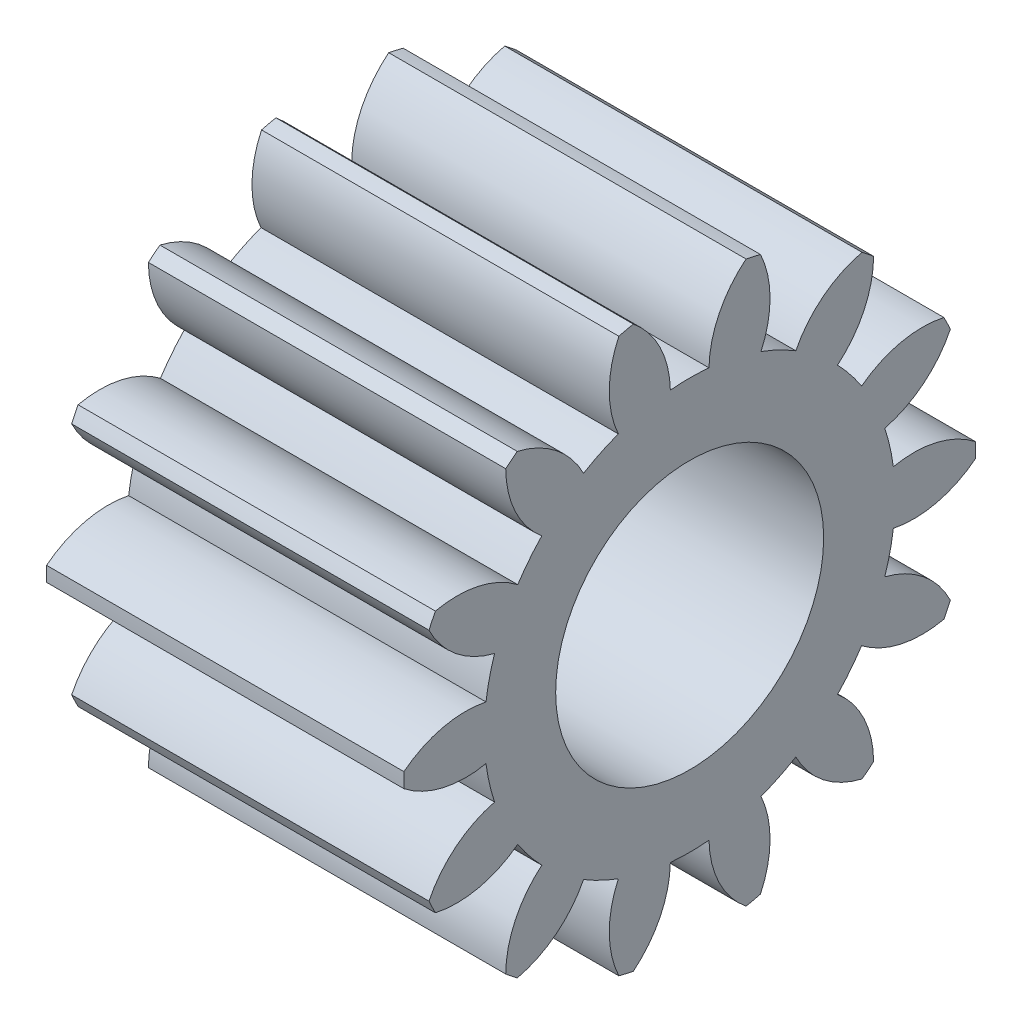
SolidWorks part; units mm, degrees
ref_plane "Plane1" through (0, 0, 0) normal (0, 0, 1) x (1, 0, 0)
ref_plane "Plane2" through (0, 0, 0) normal (0, 1, 0) x (1, 0, 0)
ref_plane "Plane3" through (0, 0, 0) normal (1, 0, 0) x (0, 0, -1)
other "Configuration Table"
sketch "HoldingSke" plane through (0, 0, 0) normal (0, 1, 0) x (1, 0, 0)
  line L0 (0, 0) -> (0.9703, -0.2419)
  line L1 (-15, 0) -> (100, 0) construction
  line L2 (0, 0) -> (-2.1039, 2.3779)
  line L3 (0, 0) -> (-11.863, 4.5341)
  line L4 (0, 0) -> (8.3795, 2.0892)
  line L5 (0, 0) -> (-46.8476, -17.4728)
  line L6 (0, 0) -> (-8.2896, -5.593)
  line L7 (-2.1039, 2.3779) -> (8.6586, 51.2059)
  line L8 (-76.2, 54.61) -> (-76.1, 54.61)
  line L9 (-71.009, 38.7566) -> (-53.1078, 45.2721)
  line L10 (-76.2, 71.12) -> (104.1128, 71.12)
  line L11 (0, 0) -> (-10, 0)
  line L12 (-76.2, 101.6) -> (-76.162, 101.6)
  line L13 (24.9733, 27.94) -> (52.9518, 28.4284)
  line L14 (24.9733, 27.94) -> (24.9743, 27.94)
  line L15 (24.9733, 27.94) -> (100.4006, 29.5858)
  line L16 (-63.627, -1) -> (-12.827, -1)
  circle A0 centre (0, 0) radius 0.5
  circle A1 centre (0, 0) radius 5.749
  circle A2 centre (0, 0) radius 37.5
  circle A3 centre (0, 0) radius 0.5
  dimension "MHD" = 11.498
  dimension "Hub_dia" = 75
  dimension "Bore" = 1
  dimension "MBD" = 1
  dimension "Num_teeth" = 14
  dimension "Pitch" = 1
  dimension "Overall_len" = 50
  dimension "Show_teeth" = 14
  dimension "Thickness" = 10
  dimension "OAL" = 50.0001
  dimension "T_dim" = 0.1
  dimension "Ap" = 20
  dimension "H" = 19.05
  dimension "Pitch_radius" = 180.3128
  dimension "Width" = 10
  dimension "Backlash" = 0.038
  dimension "Addendum_fac" = 1
  dimension "Dedendum_fac" = 1.25
  dimension "Clearance_fac" = 0.25
  dimension "Dedendum_add" = 0.001
  dimension "Module" = 1
sketch "BasProSke" plane through (0, 0, 0) normal (0, 1, 0) x (1, 0, 0)
  line L0 (-10, 0) -> (60, 0) construction
  line L1 (0, 0) -> (0, 8)
  line L2 (0, 0) -> (10, 0)
  line L3 (10, 0) -> (10, 8)
  line L4 (10, 8) -> (0, 8)
  dimension "Thickness" = 10
  dimension "Diameter" = 16
revolve "Base-Revolve" add sketch "BasProSke" angle 360 about L0
sketch "TooCutSke" plane through (0, 0, 0) normal (1, 0, 0) x (0, 0, -1)
  line L1 (0, 0) -> (0, 107) construction
  line L2 (0, 0) -> (-0.8502, 6.9482) construction
  line L3 (0, 0) -> (-3.0989, 13.5772) construction
  line L4 (-0.8502, 6.9482) -> (-1.5494, 6.7886) construction
  arc A0 (0.5404, 5.7235) -> (-0.5404, 5.7235) centre (0, 0) ccw
  arc A1 (1.6036, 7.8636) -> (-1.6036, 7.8636) centre (0, 0) ccw
  circle A2 centre (0, 0) radius 7 construction
  circle A3 centre (0, 0) radius 6.5778 construction
  arc A4 (-0.5404, 5.7235) -> (-1.6036, 7.8636) centre (-3.3398, 5.6669) ccw
  arc A5 (1.6036, 7.8636) -> (0.5404, 5.7235) centre (3.3398, 5.6669) ccw
  dimension "Root_dia" = 11.498
  dimension "Overcut_dia" = 16.0508
  dimension "Pitch_dia" = 14
  dimension "Base_dia" = 13.1557
  dimension "Flank_rad" = 2.8
  dimension "Half_ang" = 12.857
  dimension "Half_CT" = 0.7173
extrude "ToothCut" cut sketch "TooCutSke" along normal through all
fillet "Breaks" [suppressed] radius 0.02
fillet "RootFillets" [suppressed] radius 0.251
pattern_circular "TeethCuts" count 14 every 25.714 about axis through (-10, 0, 0) along (1, 0, 0) of "ToothCut", "RootFillets", "Breaks"
sketch "HubNeaOneSke" plane through (0, 0, 0) normal (-1, 0, 0) x (0, 0, 1)
  circle A0 centre (0, 0) radius 5.749
  dimension "Diameter" = 11.498
extrude "HubNearOne" [suppressed] add sketch "HubNeaOneSke" along normal blind 40.0001
sketch "HubNeaBotSke" plane through (0, 0, 0) normal (-1, 0, 0) x (0, 0, 1)
  circle A0 centre (0, 0) radius 5.749
  dimension "Diameter" = 11.498
extrude "HubNearBoth" [suppressed] add sketch "HubNeaBotSke" along normal blind 20
ref_plane "FarPln" through (10, 0, 0) normal (1, 0, 0) x (0, 0, -1)
sketch "HubFarSke" plane through (10, 0, 0) normal (1, 0, 0) x (0, 0, -1)
  circle A0 centre (0, 0) radius 5.749
  dimension "Diameter" = 11.498
extrude "HubFar" [suppressed] add sketch "HubFarSke" along normal blind 20
sketch "BorSke" plane through (0, 0, 0) normal (1, 0, 0) x (0, 0, -1)
  circle A0 centre (0, 0) radius 0.5
  dimension "Diameter" = 1
extrude "Bore" cut sketch "BorSke" along normal mid plane 100.0001
sketch "KeySke" plane through (0, 0, 0) normal (1, 0, 0) x (0, 0, -1)
  line L0 (-0.05, 0) -> (-0.05, 0.6)
  line L1 (-0.05, 0.6) -> (0.05, 0.6)
  line L2 (0.05, 0.6) -> (0.05, 0)
  line L3 (0, 0) -> (0, 34) construction
  line L4 (-0.05, 0) -> (0.05, 0)
  dimension "Offset" = 0.6
  dimension "Width" = 0.1
extrude "Keyway" [suppressed] cut sketch "KeySke" along normal mid plane 100.0001
pattern_circular "Keyway2" [suppressed] count 2 every 90 about axis through (-10, 0, 0) along (1, 0, 0)
sketch "Sketch1" plane through (10, 0, 0) normal (1, 0, 0) x (0, 0, -1)
  line L0 (0, 5.749) -> (0, -5.749) construction
  line L1 (8, 0) -> (-8, 0) construction
  line L2 (-1.125, -1.125) -> (-1.125, -3.375)
  line L3 (-1.125, 3.375) -> (1.125, 3.375)
  line L4 (-1.125, 3.375) -> (-1.125, 1.125)
  line L5 (-1.125, -3.375) -> (1.125, -3.375)
  line L6 (1.125, 3.375) -> (1.125, 1.125)
  line L7 (3.375, -1.125) -> (1.125, -1.125)
  line L8 (3.375, -1.125) -> (3.375, 1.125)
  line L9 (3.375, 1.125) -> (1.125, 1.125)
  line L10 (-3.375, -1.125) -> (-3.375, 1.125)
  line L11 (-1.125, -1.125) -> (-3.375, -1.125)
  line L12 (1.125, -1.125) -> (1.125, -3.375)
  line L13 (-1.125, 1.125) -> (-3.375, 1.125)
  arc A0 (0.5404, 5.7235) -> (-0.5404, 5.7235) centre (0, 0) ccw construction
  arc A1 (-0.5404, -5.7235) -> (0.5404, -5.7235) centre (0, 0) ccw construction
  arc A2 (7.9973, -0.2071) -> (7.9973, 0.2071) centre (0, 0) ccw construction
  arc A3 (-7.9973, 0.2071) -> (-7.9973, -0.2071) centre (0, 0) ccw construction
  point P16 (0, 0)
  dimension "D1" = 6.75
extrude "Cut-Extrude1" cut sketch "Sketch1" against normal through all
sketch "Sketch2" plane through (10, 0, 0) normal (1, 0, 0) x (0, 0, -1)
  circle A0 centre (0, 0) radius 3.75
  dimension "D1" = 7.5
extrude "Cut-Extrude2" cut sketch "Sketch2" against normal through all both and the other way through all
equation "' \"Module@HoldingSke\" = 6.35"
equation "' \"Num_teeth@HoldingSke\" = 12"
equation "' \"Ap@HoldingSke\" =  20"
equation "' \"Ap@HoldingSke\" = 20"
equation "' \"Width@HoldingSke\" = 0.5 * 25.4"
equation "' \"Hub_dia@HoldingSke\"= 1 * 25.4"
equation "' \"Hub_dia@HoldingSke\" = 1 * 25.4"
equation "' \"Overall_len@HoldingSke\" = 1.0 * 25.4"
equation "' \"Bore@HoldingSke\" = 0.75 * 25.4"
equation "' \"T_dim@HoldingSke\" = 0.1 * 25.4"
equation "' \"Width@KeySke\" = 0.25 * 25.4"
equation "' \"Show_teeth@HoldingSke\" = 13"
equation "' \"Backlash@HoldingSke\" = 0.009 * 25.4"
equation "' \"Addendum_fac@HoldingSke\" = 1.0"
equation "' \"Dedendum_fac@HoldingSke\" = 1.25"
equation "' \"Dedendum_add@HoldingSke\" = 0.00005 * 25.4"
equation "' \"Clearance_fac@HoldingSke\" = 0.25"
equation "\"Pitch@HoldingSke\" = 1 / \"Module@HoldingSke\""
equation "\"Overcut_dia@TooCutSke\" = (\"Num_teeth@HoldingSke\" + 2 * \"Addendum_fac@HoldingSke\") / \"Pitch@HoldingSke\" + 0.002 * 25.4"
equation "\"Pitch_dia@TooCutSke\" = \"Num_teeth@HoldingSke\" / \"Pitch@HoldingSke\""
equation "\"Base_dia@TooCutSke\" = \"Num_teeth@HoldingSke\" / \"Pitch@HoldingSke\" * cos((\"Ap@HoldingSke\"  * 3.14159265 / 180))"
equation "\"Root_dia@TooCutSke\" = (\"Num_teeth@HoldingSke\" + 2) / \"Pitch@HoldingSke\" - 2 * (\"Addendum_fac@HoldingSke\" + \"Dedendum_fac@HoldingSke\") / \"Pitch@HoldingSke\" - \"Dedendum_add@HoldingSke\" * 2"
equation "\"Half_ang@TooCutSke\" = 180 / \"Num_teeth@HoldingSke\""
equation "\"Half_CT@TooCutSke\" = \"Num_teeth@HoldingSke\" / \"Pitch@HoldingSke\" * sin((3.14159265 / 2 / \"Num_teeth@HoldingSke\")) / 2 - 7 * \"Backlash@HoldingSke\" / 4"
equation "\"Flank_rad@TooCutSke\" = \"Num_teeth@HoldingSke\" / \"Pitch@HoldingSke\" / 5"
equation "\"Radius@RootFillets\" = \"Clearance_fac@HoldingSke\" / \"Pitch@HoldingSke\" + \"Dedendum_add@HoldingSke\""
equation "\"Break_rad@Breaks\" = 0.02 / \"Pitch@HoldingSke\""
equation "\"Thickness@HoldingSke\" = \"Width@HoldingSke\""
equation "\"OAL@HoldingSke\" = \"Thickness@HoldingSke\""
equation "\"MHD@HoldingSke\" = (\"Num_teeth@HoldingSke\" + 2) / \"Pitch@HoldingSke\" - 2 * (\"Addendum_fac@HoldingSke\" + \"Dedendum_fac@HoldingSke\")  / \"Pitch@HoldingSke\" - \"Dedendum_add@HoldingSke\" * 2"
equation "\"MBD@HoldingSke\" = (\"Num_teeth@HoldingSke\" + 2) / \"Pitch@HoldingSke\" - 2 * (\"Addendum_fac@HoldingSke\" + \"Dedendum_fac@HoldingSke\")  / \"Pitch@HoldingSke\" - \"Dedendum_add@HoldingSke\" * 2 - 0.002 * 25.4"
equation "\"MHD@HoldingSke\" = ((sgn( \"MHD@HoldingSke\" - \"Hub_dia@HoldingSke\" )-1)*( \"MHD@HoldingSke\" - \"Hub_dia@HoldingSke\" ))/-2+ \"Hub_dia@HoldingSke\""
equation "\"MBD@HoldingSke\" = ((sgn( \"MBD@HoldingSke\" - \"Bore@HoldingSke\" )-1)*( \"MBD@HoldingSke\" - \"Bore@HoldingSke\" ))/-2+ \"Bore@HoldingSke\""
equation "\"OAL@HoldingSke\" = ((sgn( \"OAL@HoldingSke\" - \"Overall_len@HoldingSke\" )+1)*( \"OAL@HoldingSke\" - \"Overall_len@HoldingSke\" ))/2 + \"Overall_len@HoldingSke\" + 0.000002 * 25.4"
equation "\"Num_teeth@TeethCuts\" = int( \"Show_teeth@HoldingSke\" ) + 1"
equation "\"Num_teeth@TeethCuts\" = ((sgn( \"Num_teeth@TeethCuts\" - \"Num_teeth@HoldingSke\" )-1)*( \"Num_teeth@TeethCuts\" - \"Num_teeth@HoldingSke\" ))/-2+ \"Num_teeth@HoldingSke\""
equation "\"Num_teeth@TeethCuts\" = ((sgn( \"Num_teeth@TeethCuts\" - 2.0)+1)*( \"Num_teeth@TeethCuts\" - 2.0))/2 +2.0"
equation "\"Angle@TeethCuts\" = 360.0 / \"Num_teeth@HoldingSke\""
equation "\"Diameter@BasProSke\" = (\"Num_teeth@HoldingSke\" + 2 * \"Addendum_fac@HoldingSke\") / \"Pitch@HoldingSke\""
equation "\"Thickness@BasProSke\"  = \"Thickness@HoldingSke\""
equation "' \"Fillet_rad@BasProSke\" =  \"Thickness@HoldingSke\" * 0.05"
equation "' \"Fillet_rad@BasProSke\" = \"Thickness@HoldingSke\" * 0.05"
equation "\"MHD@HoldingSke\" = ((sgn( \"MHD@HoldingSke\" - \"Root_dia@TooCutSke\" )-1)*( \"MHD@HoldingSke\" - \"Root_dia@TooCutSke\" ))/-2+ \"Root_dia@TooCutSke\""
equation "\"Diameter@HubNeaOneSke\" = \"MHD@HoldingSke\""
equation "\"Length@HubNearOne\" = \"OAL@HoldingSke\" - \"Thickness@BasProSke\""
equation "\"Diameter@HubNeaBotSke\" = \"MHD@HoldingSke\""
equation "\"Length@HubNearBoth\" = ( \"OAL@HoldingSke\" - \"Thickness@BasProSke\" ) / 2.0"
equation "\"Thickness@FarPln\" = \"Thickness@BasProSke\""
equation "\"Diameter@HubFarSke\" = \"MHD@HoldingSke\""
equation "\"Length@HubFar\" = ( \"OAL@HoldingSke\" - \"Thickness@BasProSke\" ) / 2.0"
equation "\"Diameter@BorSke\" = \"MBD@HoldingSke\""
equation "\"D1@Bore\" = \"OAL@HoldingSke\" * 2.0"
equation "\"D1@Keyway\" = \"OAL@HoldingSke\" * 2.0"
equation "\"Offset@KeySke\" = \"T_dim@HoldingSke\" + \"MBD@HoldingSke\" / 2.0"
